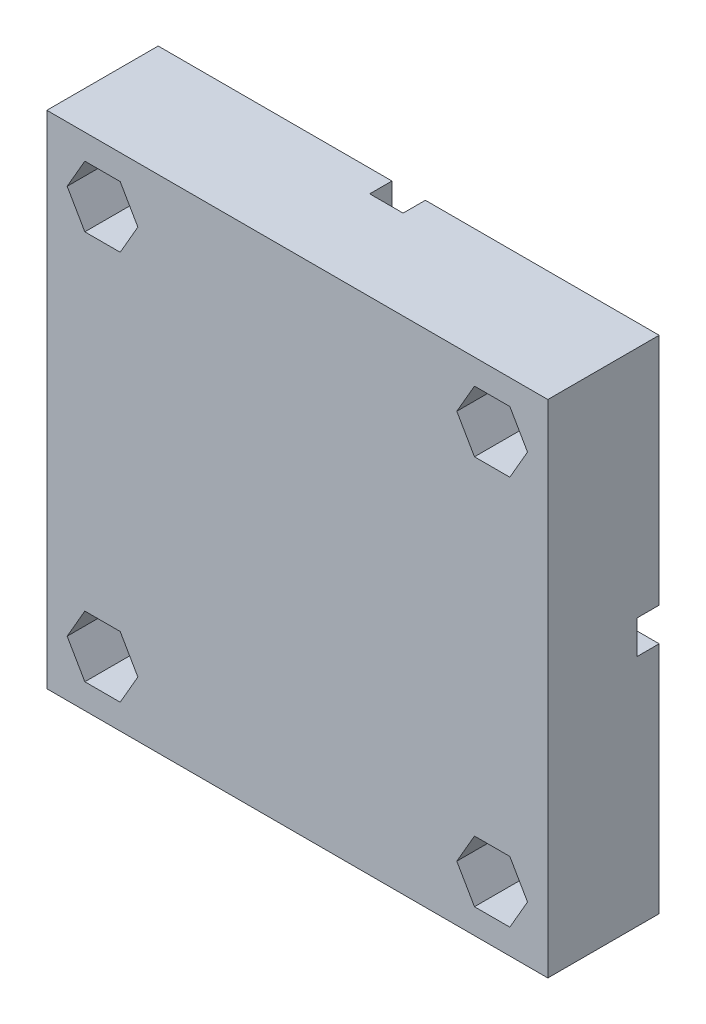
SolidWorks part; units mm, degrees
ref_plane "Front Plane" through (0, 0, 0) normal (0, 0, 1) x (1, 0, 0)
ref_plane "Top Plane" through (0, 0, 0) normal (0, 1, 0) x (1, 0, 0)
ref_plane "Right Plane" through (0, 0, 0) normal (1, 0, 0) x (0, 0, -1)
sketch "Sketch1" plane through (0, 0, 0) normal (0, 0, 1) x (1, 0, 0)
  line L1 (0, 0) -> (45, 0)
  line L2 (0, 0) -> (0, 45)
  line L3 (0, 45) -> (45, 45)
  line L4 (45, 0) -> (45, 45)
  line L5 (5, 5) -> (40, 5) construction
  line L6 (5, 5) -> (5, 40) construction
  line L7 (5, 40) -> (40, 40) construction
  line L8 (40, 5) -> (40, 40) construction
  line L9 (5, 5) -> (40, 40) construction
  line L10 (5, 40) -> (40, 5) construction
  line L11 (8.1754, 40) -> (6.5877, 42.75) construction
  line L12 (6.5877, 42.75) -> (3.4123, 42.75) construction
  line L13 (3.4123, 42.75) -> (1.8246, 40) construction
  line L14 (1.8246, 40) -> (3.4123, 37.25) construction
  line L15 (3.4123, 37.25) -> (6.5877, 37.25) construction
  line L16 (6.5877, 37.25) -> (8.1754, 40) construction
  circle A0 centre (5, 5) radius 1.6
  circle A1 centre (5, 40) radius 1.6
  circle A2 centre (40, 40) radius 1.6
  circle A3 centre (40, 5) radius 1.6
  circle A4 centre (5, 40) radius 2.75 construction
  point P10 (22.5, 22.5)
  dimension "D3" = 3.2
  dimension "D4" = 3.2
  dimension "D5" = 3.2
  dimension "D6" = 3.2
  dimension "D1" = 45
  dimension "D2" = 45
  dimension "D7" = 5
  dimension "D8" = 5
  dimension "D9" = 5
  dimension "D10" = 5
  dimension "D11" = 5.5
extrude "Boss-Extrude1" add sketch "Sketch1" along normal blind 10
sketch "Sketch2" plane through (0, 0, 10) normal (0, 0, 1) x (1, 0, 0)
  line L1 (8.1754, 5) -> (6.5877, 7.75)
  line L2 (6.5877, 7.75) -> (3.4123, 7.75)
  line L3 (3.4123, 7.75) -> (1.8246, 5)
  line L4 (1.8246, 5) -> (3.4123, 2.25)
  line L5 (3.4123, 2.25) -> (6.5877, 2.25)
  line L6 (6.5877, 2.25) -> (8.1754, 5)
  line L7 (8.1754, 40) -> (6.5877, 42.75)
  line L8 (6.5877, 42.75) -> (3.4123, 42.75)
  line L9 (3.4123, 42.75) -> (1.8246, 40)
  line L10 (1.8246, 40) -> (3.4123, 37.25)
  line L11 (3.4123, 37.25) -> (6.5877, 37.25)
  line L12 (6.5877, 37.25) -> (8.1754, 40)
  line L13 (43.1754, 40) -> (41.5877, 42.75)
  line L14 (41.5877, 42.75) -> (38.4123, 42.75)
  line L15 (38.4123, 42.75) -> (36.8246, 40)
  line L16 (36.8246, 40) -> (38.4123, 37.25)
  line L17 (38.4123, 37.25) -> (41.5877, 37.25)
  line L18 (41.5877, 37.25) -> (43.1754, 40)
  line L19 (43.1754, 5) -> (41.5877, 7.75)
  line L20 (41.5877, 7.75) -> (38.4123, 7.75)
  line L21 (38.4123, 7.75) -> (36.8246, 5)
  line L22 (36.8246, 5) -> (38.4123, 2.25)
  line L23 (38.4123, 2.25) -> (41.5877, 2.25)
  line L24 (41.5877, 2.25) -> (43.1754, 5)
  circle A0 centre (5, 5) radius 2.75 construction
  circle A1 centre (5, 40) radius 2.75 construction
  circle A2 centre (40, 40) radius 2.75 construction
  circle A3 centre (40, 5) radius 2.75 construction
  dimension "D1" = 5.5
  dimension "D2" = 5.5
  dimension "D3" = 5.5
  dimension "D4" = 5.5
extrude "Cut-Extrude1" cut sketch "Sketch2" against normal blind 5
sketch "Sketch3" plane through (0, 0, 0) normal (0, 0, -1) x (-1, 0, 0)
  line L0 (-45, 24) -> (-24, 24)
  line L1 (-45, 0) -> (-45, 45) construction
  line L2 (-24, 24) -> (-24, 45)
  line L3 (-45, 45) -> (0, 45) construction
  line L4 (-24, 45) -> (-21, 45)
  line L5 (-21, 45) -> (-21, 24)
  line L6 (-21, 24) -> (0, 24)
  line L7 (0, 45) -> (0, 0) construction
  line L8 (0, 24) -> (0, 21)
  line L9 (0, 21) -> (-21, 21)
  line L10 (-21, 21) -> (-21, 0)
  line L11 (0, 0) -> (-45, 0) construction
  line L12 (-21, 0) -> (-24, 0)
  line L13 (-24, 0) -> (-24, 21)
  line L14 (-24, 21) -> (-45, 21)
  line L15 (-45, 21) -> (-45, 24)
  point P12 (-22.5, 0)
  point P21 (-22.5, 0)
  point P22 (-45, 22.5)
  point P23 (0, 0)
  point P24 (-45, 22.5)
  point P25 (0, 0)
  dimension "D1" = 3
  dimension "D2" = 3
extrude "Cut-Extrude2" cut sketch "Sketch3" against normal blind 2
